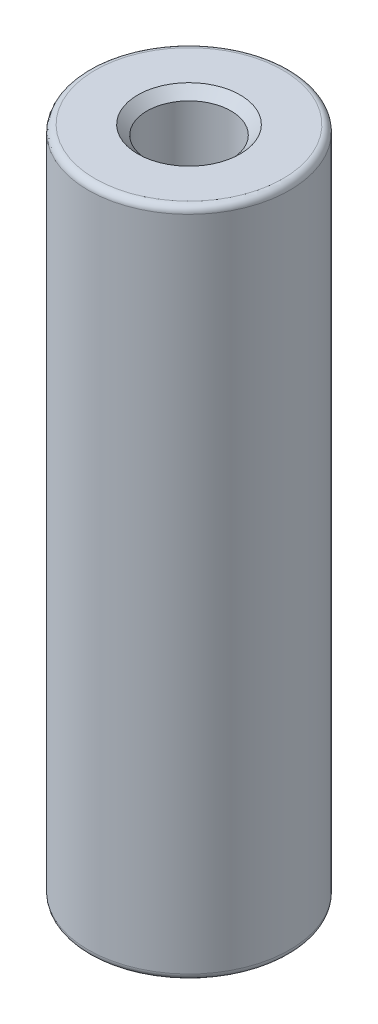
SolidWorks part; units mm, degrees
material "6061 Alloy"
ref_plane "Front Plane" through (0, 0, 0) normal (0, 0, 1) x (1, 0, 0)
ref_plane "Top Plane" through (0, 0, 0) normal (0, 1, 0) x (1, 0, 0)
ref_plane "Right Plane" through (0, 0, 0) normal (1, 0, 0) x (0, 0, -1)
sketch "Sketch1" plane through (0, 0, 0) normal (0, 1, 0) x (1, 0, 0)
  circle A0 centre (0, 0) radius 3
  dimension "D1" = 6
extrude "Boss-Extrude1" add sketch "Sketch1" along normal blind 20 contours A0
fillet "Fillet1" radius 0.2 2 edges at (0, 0, 3) (0, 20, 3)
sketch "Sketch2" plane through (0, 20, 0) normal (0, 1, 0) x (1, 0, 0)
  point P0 (0, 0)
hole_wizard "M3x0.5 Tapped Hole1" positions "Sketch2" profile "Sketch3" tap size "M3x0.5" standard "ANSI Metric" end condition through all
sketch "Sketch3" plane through (0, 20, 0) normal (1, 0, 0) x (0, 0, 1)
  line L0 (0, 0) -> (0, 20)
  line L1 (0, 20) -> (1.525, 20)
  line L2 (1.25, 19.725) -> (1.25, 0.275)
  line L3 (1.25, 0.275) -> (1.525, 0)
  line L5 (1.525, 0) -> (0, 0)
  line L6 (-1.25, 0.275) -> (-1.525, 0) construction
  line L7 (1.525, 20) -> (1.25, 19.725)
  line L8 (-1.525, 20) -> (-1.25, 19.725) construction
  line L11 (0, -6.35) -> (0, 107.95) construction
  dimension "Thru Tap Drill Dia." = 2.5
  dimension "Thru Tap Drill Depth" = 20
  dimension "Near C'Sink Dia." = 3.05
  dimension "Near C'Sink Angle" = 90
  dimension "Far C'Sink Dia." = 3.05
  dimension "Far C'Sink Angle" = 90
cosmetic thread "Hole Thread1"
